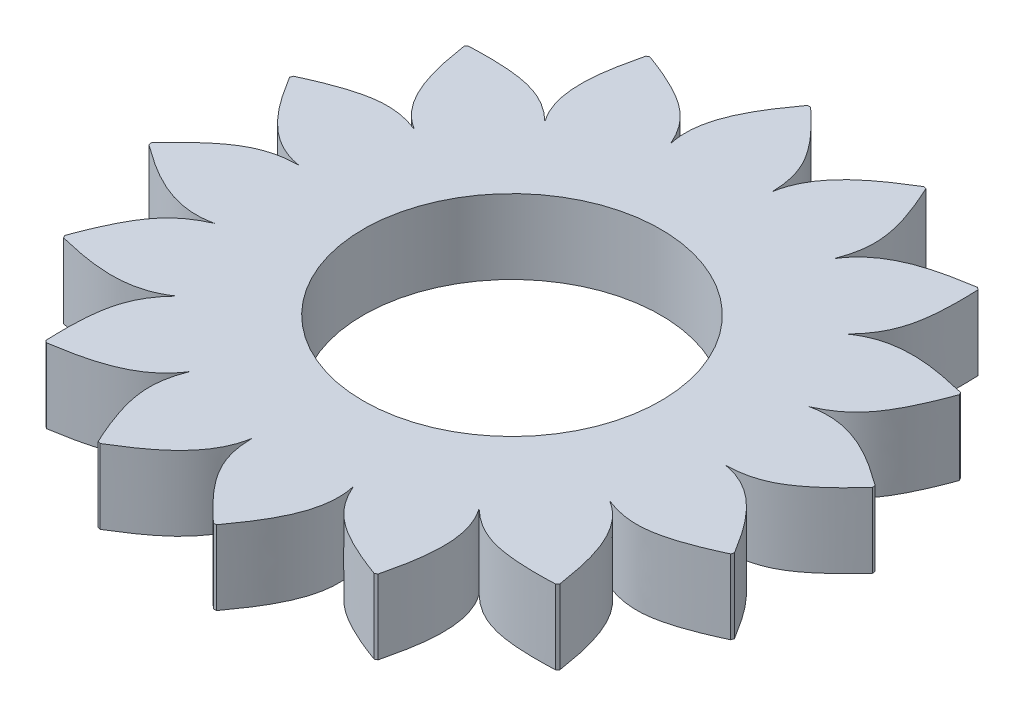
SolidWorks part; units mm, degrees
ref_plane "Front Plane" through (0, 0, 0) normal (0, 0, 1) x (1, 0, 0)
ref_plane "Top Plane" through (0, 0, 0) normal (0, 1, 0) x (1, 0, 0)
ref_plane "Right Plane" through (0, 0, 0) normal (1, 0, 0) x (0, 0, -1)
sketch "Sketch1" plane through (0, 0, 0) normal (0, 1, 0) x (1, 0, 0)
  line L0 (0, 0) -> (0, 42.4764) construction
  line L1 (-20.1351, 25.4) -> (20.1351, 25.4) construction
  line L2 (-16.3211, 12.8764) -> (16.5941, 38.1331) construction
  line L3 (0, 0) -> (-12.2673, 15.987) construction
  line L4 (0, 0) -> (-15.468, 12.9156) construction
  line L5 (-15.468, 12.9156) -> (-2.7085, 28.1965) construction
  line L6 (0, 0) -> (-9.0439, 18.0077) construction
  line L7 (-9.0439, 18.0077) -> (1.3691, 23.2374) construction
  line L8 (-9.0439, 18.0077) -> (0, 25.4) construction
  circle A0 centre (0, 0) radius 25.4 construction
  circle A1 centre (0, 0) radius 20.1512 construction
  arc A2 (-12.2673, 15.987) -> (-15.468, 12.9156) centre (0, 0) ccw
  arc A3 (-12.2673, 15.987) -> (-9.0439, 18.0077) centre (0, 0) cw
  point P10 (0, 25.4)
  point P14 (0, 0)
  dimension "D1" = 50.8
  dimension "D2" = 37.5
  dimension "D3" = 15.4625
  dimension "D5" = 19.9075
  dimension "D7" = 11.6525
  dimension "D4" = 4.445
  dimension "D6" = 3.81
sketch "Sketch2" plane through (0, 0, 0) normal (0, 1, 0) x (1, 0, 0)
  line L0 (0, 0) -> (-3.422, 34.7447) construction
  line L1 (0, 0) -> (0, 42.4764) construction
  line L2 (1.9885, 20.0528) -> (1.9885, 19.7988)
  line L3 (-5.8624, 19.2796) -> (-5.8128, 19.0305)
  circle A0 centre (0, 0) radius 20.1512 construction
  arc A1 (-2.6409, 28.1338) -> (-2.8985, 28.1085) centre (0, 0) ccw
  arc A2 (1.9885, 19.7988) -> (-5.8128, 19.0305) centre (0, 0) ccw
  circle A3 centre (0, 0) radius 19.8984
  spline S0 degree 3 poles (-2.6409, 28.1338) (-1.7474, 27.3046) (-0.1759, 25.7918) (1.647, 23.0952) (1.9885, 21.2076) (1.9885, 20.0528) knots 0.009893 0.009893 0.009893 0.009893 0.401482 0.665436 1 1 1 1
  spline S1 degree 3 poles (-2.8985, 28.1085) (-3.613, 27.1209) (-5.5105, 24.4133) (-6.3937, 21.2759) (-5.8624, 19.2796) knots 0.009893 0.009893 0.009893 0.009893 0.401482 1 1 1 1
  dimension "D2" = 56.515
  dimension "D1" = 5.625
  dimension "D3" = 0.254
sketch "Sketch3" plane through (0, 0, 0) normal (0, 1, 0) x (1, 0, 0)
  circle A0 centre (0, 0) radius 19.8984 construction
  circle A1 centre (0, 0) radius 19.8984
extrude "Boss-Extrude1" add sketch "Sketch3" along normal blind 6.35
sketch "Sketch4" plane through (0, 0, 0) normal (0, 1, 0) x (1, 0, 0)
  line L2 (1.9885, 20.0528) -> (1.9885, 19.7988) construction
  line L3 (-5.8624, 19.2796) -> (-5.8128, 19.0305) construction
  line L4 (1.9885, 20.0528) -> (1.9885, 19.7988)
  line L5 (-5.8624, 19.2796) -> (-5.8128, 19.0305)
  arc A1 (1.9885, 19.7988) -> (-5.8128, 19.0305) centre (0, 0) ccw construction
  arc A2 (-2.6409, 28.1338) -> (-2.8985, 28.1085) centre (0, 0) ccw construction
  arc A3 (1.9885, 19.7988) -> (-5.8128, 19.0305) centre (0, 0) ccw
  arc A4 (-2.6409, 28.1338) -> (-2.8985, 28.1085) centre (0, 0) ccw
  spline S2 degree 3 poles (2981.9872, 330.2094) (-135.6146, 9.6126) (-18.6779, 53.1626) (26.8371, -14.1695) (-379.8048, -199.6169) (2241.8868, -1934.8525) knots -10.039498 -10.039498 -10.039498 -10.039498 0.401482 0.665436 14.682028 14.682028 14.682028 14.682028 only from (-2.6409, 28.1338) to (1.9885, 20.0528) construction
  spline S3 degree 3 poles (-2985.1381, -297.1266) (131.2303, 38.8773) (-103.1337, 68.732) (59.3895, -69.6122) (2992.3161, 51.8403) knots -9.703395 -9.703395 -9.703395 -9.703395 0.401482 9.882554 9.882554 9.882554 9.882554 only from (-2.8985, 28.1085) to (-5.8624, 19.2796) construction
  spline S4 degree 3 poles (-2.6409, 28.1338) (-1.7474, 27.3046) (-0.1759, 25.7918) (1.647, 23.0952) (1.9885, 21.2076) (1.9885, 20.0528) knots 0.009893 0.009893 0.009893 0.009893 0.401482 0.665436 1 1 1 1
  spline S5 degree 3 poles (-2.8985, 28.1085) (-3.613, 27.1209) (-5.5105, 24.4133) (-6.3937, 21.2759) (-5.8624, 19.2796) knots 0.009893 0.009893 0.009893 0.009893 0.401482 1 1 1 1
extrude "Boss-Extrude2" add sketch "Sketch4" along normal up to surface (6.35 mm away) up to face at (0, 6.35, 19.8984)
pattern_circular "CirPattern1" count 16 over 360 about axis through (0, 6.35, 0) along (0, -1, 0) of "Boss-Extrude2"
sketch "Sketch5" plane through (0, 6.35, 0) normal (0, 1, 0) x (1, 0, 0)
  circle A0 centre (0, 0) radius 12.7
  dimension "D1" = 25.4
extrude "Cut-Extrude1" cut sketch "Sketch5" against normal through all
equation "\"D5@Sketch1\"=\"D3@Sketch1\"+\"D4@Sketch1\""
equation "\"D7@Sketch1\"=\"D3@Sketch1\"-\"D6@Sketch1\""
equation "\"D1@Sketch2\"=360/16/4"
